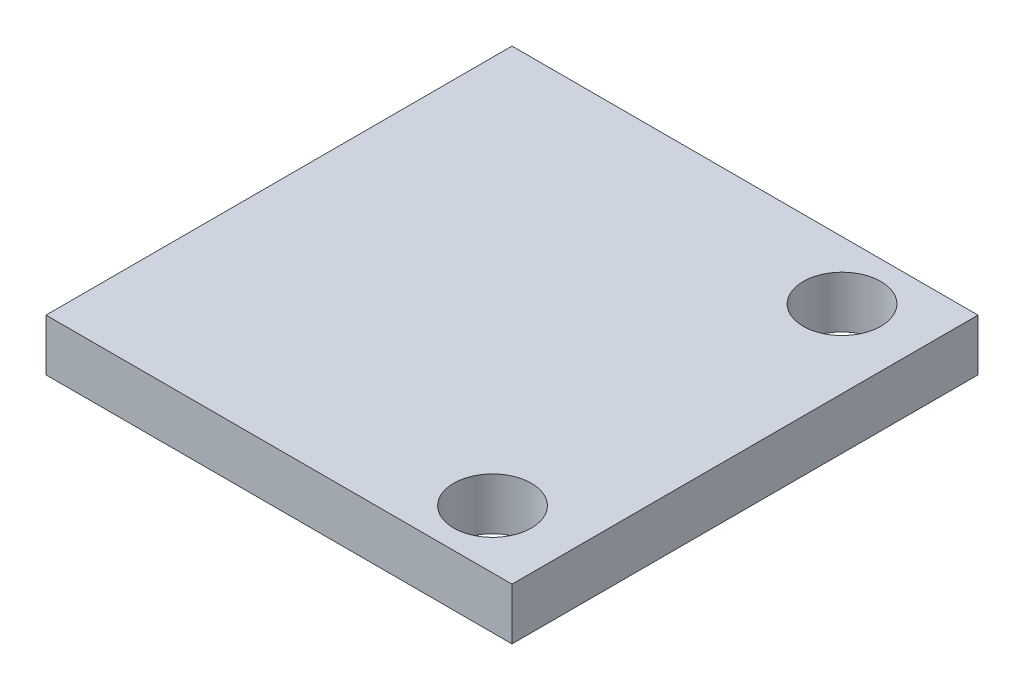
SolidWorks part; units mm, degrees
ref_plane "Front Plane" through (0, 0, 0) normal (0, 0, 1) x (1, 0, 0)
ref_plane "Top Plane" through (0, 0, 0) normal (0, 1, 0) x (1, 0, 0)
ref_plane "Right Plane" through (0, 0, 0) normal (1, 0, 0) x (0, 0, -1)
sketch "Sketch1" plane through (0, 0, 0) normal (0, 1, 0) x (1, 0, 0)
  line L1 (5.4692, 7.7967) -> (23.4692, 7.7967)
  line L2 (5.4692, 7.7967) -> (5.4692, -10.2033)
  line L3 (5.4692, -10.2033) -> (23.4692, -10.2033)
  line L4 (23.4692, 7.7967) -> (23.4692, -10.2033)
  dimension "D1" = 18
  dimension "D2" = 18
extrude "Boss-Extrude1" add sketch "Sketch1" along normal blind 2 contours L2 L1 L4 L3
sketch "Sketch2" plane through (0, 2, 0) normal (0, 1, 0) x (1, 0, 0)
  circle A0 centre (20.4674, 5.5467) radius 1.5
  circle A1 centre (20.4674, -7.9533) radius 1.5
  dimension "D1" = 3
  dimension "D2" = 3
extrude "Cut-Extrude1" cut sketch "Sketch2" against normal through all
